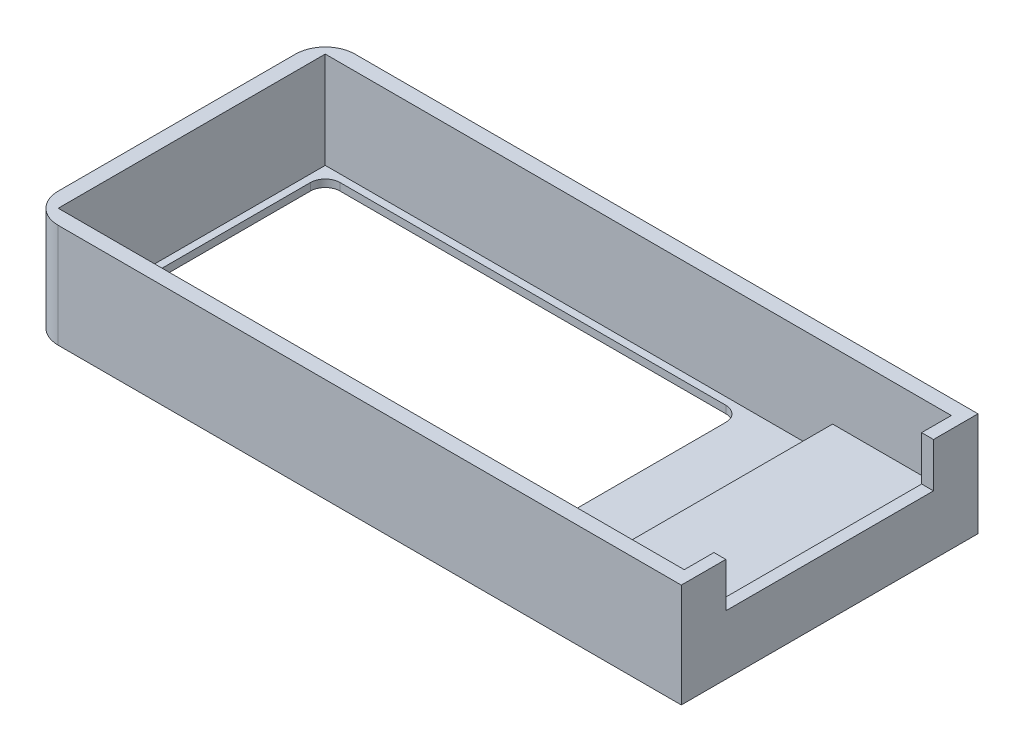
SolidWorks part; units mm, degrees
ref_plane "Front Plane" through (0, 0, 0) normal (0, 0, 1) x (1, 0, 0)
ref_plane "Top Plane" through (0, 0, 0) normal (0, 1, 0) x (1, 0, 0)
ref_plane "Right Plane" through (0, 0, 0) normal (1, 0, 0) x (0, 0, -1)
sketch "Sketch1" plane through (0, 0, 0) normal (0, 1, 0) x (1, 0, 0)
  line L1 (0, 0) -> (44, 0)
  line L2 (0, 0) -> (0, 20)
  line L3 (0, 20) -> (44, 20)
  line L4 (44, 0) -> (44, 20)
  dimension "D1" = 44
  dimension "D2" = 20
extrude "Boss-Extrude1" add sketch "Sketch1" along normal blind 7
sketch "Sketch2" plane through (0, 7, 0) normal (0, 1, 0) x (1, 0, 0)
  line L0 (44, 20) -> (0, 20) construction
  line L1 (1, 19) -> (43.2, 19)
  line L2 (1, 19) -> (1, 1)
  line L3 (1, 1) -> (43.2, 1)
  line L4 (43.2, 19) -> (43.2, 1)
  line L5 (0, 0) -> (44, 0) construction
  line L6 (0, 20) -> (0, 0) construction
  dimension "D1" = 1
  dimension "D2" = 1
  dimension "D3" = 1
  dimension "D4" = 42.2
extrude "Cut-Extrude1" cut sketch "Sketch2" against normal blind 6.5
sketch "Sketch3" plane through (0, 0.5, 0) normal (0, 1, 0) x (1, 0, 0)
  line L0 (1, 19) -> (1, 1) construction
  line L1 (1.5, 18.5) -> (29.5, 18.5)
  line L2 (1.5, 18.5) -> (1.5, 1.5)
  line L3 (1.5, 1.5) -> (29.5, 1.5)
  line L4 (29.5, 18.5) -> (29.5, 1.5)
  line L5 (43.2, 19) -> (1, 19) construction
  line L6 (1, 1) -> (43.2, 1) construction
  dimension "D1" = 0.5
  dimension "D2" = 0.5
  dimension "D3" = 0.5
  dimension "D4" = 28
extrude "Cut-Extrude2" cut sketch "Sketch3" against normal up to next
sketch "Sketch4" plane through (0, 0.5, 0) normal (0, 1, 0) x (1, 0, 0)
  line L0 (43.2, 19) -> (1, 19) construction
  line L1 (35.2, 19) -> (43.2, 19)
  line L2 (35.2, 19) -> (35.2, 1)
  line L3 (35.2, 1) -> (43.2, 1)
  line L4 (43.2, 19) -> (43.2, 1)
  dimension "D1" = 8
extrude "Boss-Extrude2" add sketch "Sketch4" along normal blind 2
sketch "Sketch5" plane through (0, 7, 0) normal (0, 1, 0) x (1, 0, 0)
  line L0 (43.2, 1) -> (43.2, 19) construction
  line L1 (43.2, 17) -> (44, 17)
  line L2 (43.2, 17) -> (43.2, 3)
  line L3 (43.2, 3) -> (44, 3)
  line L4 (44, 17) -> (44, 3)
  line L5 (44, 0) -> (44, 20) construction
  line L6 (43.2, 19) -> (1, 19) construction
  line L7 (35.2, 1) -> (43.2, 1) construction
  dimension "D1" = 2
  dimension "D2" = 2
extrude "Cut-Extrude3" cut sketch "Sketch5" against normal blind 3
fillet "Fillet1" radius 2 2 edges at (0, 3.5, -20) (0, 3.5, 0)
fillet "Fillet2" radius 1 4 edges at (29.5, 0.25, -18.5) (29.5, 0.25, -1.5) (1.5, 0.25, -18.5) (1.5, 0.25, -1.5)
